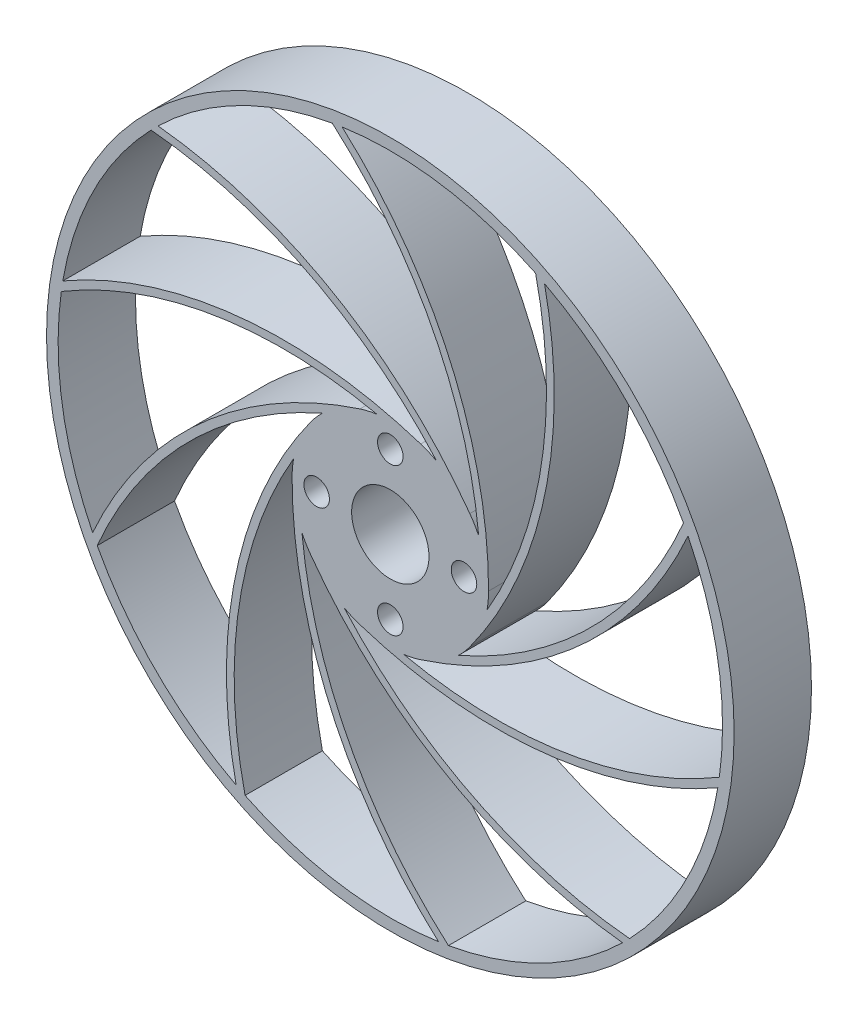
SolidWorks part; units mm, degrees
ref_plane "Front Plane" through (0, 0, 0) normal (0, 0, 1) x (1, 0, 0)
ref_plane "Top Plane" through (0, 0, 0) normal (0, 1, 0) x (1, 0, 0)
ref_plane "Right Plane" through (0, 0, 0) normal (1, 0, 0) x (0, 0, -1)
sketch "Sketch1" plane through (0, 0, 0) normal (0, 0, 1) x (1, 0, 0)
  line L0 (-9.525, 0) -> (0, 0) construction
  line L1 (0, 0) -> (9.525, 0) construction
  line L2 (0, 9.525) -> (0, 0) construction
  line L3 (0, 0) -> (0, -9.525) construction
  circle A0 centre (0, 0) radius 5
  circle A1 centre (0, 0) radius 12.7
  circle A2 centre (0, 9.525) radius 1.65
  circle A3 centre (0, -9.525) radius 1.65
  circle A4 centre (9.525, 0) radius 1.65
  circle A5 centre (-9.525, 0) radius 1.65
  circle A6 centre (0, 0) radius 44.45
  circle A7 centre (0, 0) radius 42.95
  arc A8 (-12.7, 0) -> (6.236, -42.4949) centre (44.45, 0) ccw
  arc A9 (-11.4255, -5.545) -> (7.5105, -42.2882) centre (44.45, 0) ccw
  arc A10 (-10.2745, 7.4649) -> (-19.9328, -38.0445) centre (35.9608, -26.1271) ccw
  arc A11 (-12.5027, 2.2298) -> (-18.7803, -38.6265) centre (35.9608, -26.1271) ccw
  arc A12 (-3.9245, 12.0784) -> (-38.488, -19.0624) centre (13.7358, -42.2745) ccw
  arc A13 (-8.8043, 9.1528) -> (-37.8976, -20.2107) centre (13.7358, -42.2745) ccw
  arc A14 (3.9245, 12.0784) -> (-42.3421, 7.2008) centre (-13.7358, -42.2745) ccw
  arc A15 (-1.7429, 12.5798) -> (-42.5394, 5.9249) centre (-13.7358, -42.2745) ccw
  arc A16 (10.2745, 7.4649) -> (-30.0229, 30.7136) centre (-35.9608, -26.1271) ccw
  arc A17 (5.9842, 11.2018) -> (-30.9325, 29.7973) centre (-35.9608, -26.1271) ccw
  arc A18 (12.7, 0) -> (-6.236, 42.4949) centre (-44.45, 0) ccw
  arc A19 (11.4255, 5.545) -> (-7.5105, 42.2882) centre (-44.45, 0) ccw
  arc A20 (10.2745, -7.4649) -> (19.9328, 38.0445) centre (-35.9608, 26.1271) ccw
  arc A21 (12.5027, -2.2298) -> (18.7803, 38.6265) centre (-35.9608, 26.1271) ccw
  arc A22 (3.9245, -12.0784) -> (38.488, 19.0624) centre (-13.7358, 42.2745) ccw
  arc A23 (8.8043, -9.1528) -> (37.8976, 20.2107) centre (-13.7358, 42.2745) ccw
  arc A24 (-3.9245, -12.0784) -> (42.3421, -7.2008) centre (13.7358, 42.2745) ccw
  arc A25 (1.7429, -12.5798) -> (42.5394, -5.9249) centre (13.7358, 42.2745) ccw
  arc A26 (-10.2745, -7.4649) -> (30.0229, -30.7136) centre (35.9608, 26.1271) ccw
  arc A27 (-5.9842, -11.2018) -> (30.9325, -29.7973) centre (35.9608, 26.1271) ccw
  point P18 (0, 0)
  point P66 (0, 0)
  dimension "D2" = 10
  dimension "D3" = 25.4
  dimension "D4" = 88.9
  dimension "D5" = 1.5
  dimension "D6" = 3.3
  dimension "D7" = 1
  dimension "D1" = 19.05
  dimension "D8" = 10
extrude "Boss-Extrude1" add sketch "Sketch1" along normal blind 10 contours A17 A1 A16 A7 | A19 A1 A18 A7 | A21 A1 A20 A7 | A23 A1 A22 A7 | A25 A1 A24 A7 | A27 A1 A26 A7 | A9 A1 A8 A7 | A11 A1 A10 A7 | A13 A1 A12 A7 | A15 A1 A14 A7 | A6 A7 | A1 A5 A4 A3 A2 A0
